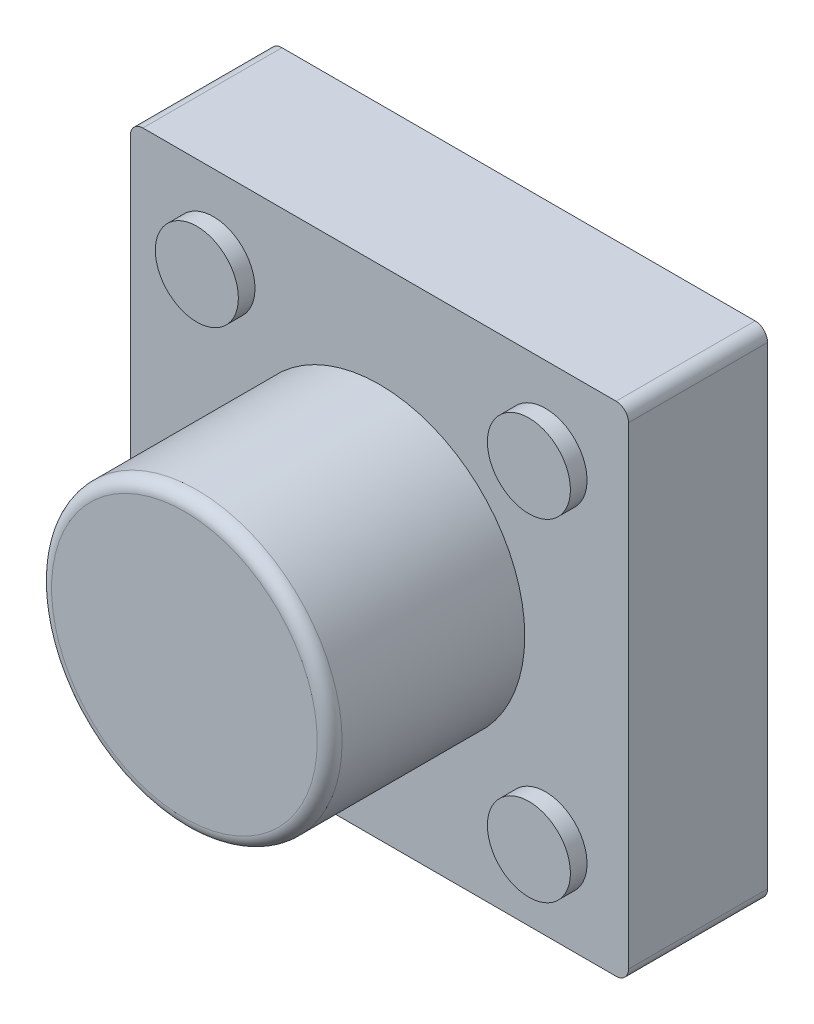
SolidWorks part; units mm, degrees
ref_plane "Front Plane" through (0, 0, 0) normal (0, 0, 1) x (1, 0, 0)
ref_plane "Top Plane" through (0, 0, 0) normal (0, 1, 0) x (1, 0, 0)
ref_plane "Right Plane" through (0, 0, 0) normal (1, 0, 0) x (0, 0, -1)
sketch "Sketch2" plane through (0, 0, 0) normal (0, 0, 1) x (1, 0, 0)
  line L1 (0, 0) -> (12, 0)
  line L2 (0, 0) -> (0, 12)
  line L3 (0, 12) -> (12, 12)
  line L4 (12, 0) -> (12, 12)
  dimension "D1" = 12
  dimension "D2" = 12
extrude "Boss-Extrude1" add sketch "Sketch2" along normal blind 3.35
sketch "Sketch3" plane through (0, 0, 3.35) normal (0, 0, 1) x (1, 0, 0)
  line L0 (6, 12) -> (6, 0) construction
  line L1 (12, 12) -> (0, 12) construction
  line L2 (0, 0) -> (12, 0) construction
  line L4 (0, 12) -> (0, 0) construction
  line L5 (0, 6) -> (12, 6) construction
  line L6 (12, 0) -> (12, 12) construction
  circle A0 centre (6, 6) radius 3.5
  dimension "D1" = 7
extrude "Boss-Extrude2" add sketch "Sketch3" along normal blind 4.7
ref_plane "Plane1" through (0, 6, 0) normal (0, 1, 0) x (1, 0, 0)
ref_plane "Plane2" through (6, 0, 0) normal (1, 0, 0) x (0, 0, -1)
ref_plane "Plane3" through (12, 0, 0) normal (1, 0, 0) x (0, 0, -1)
sketch "Sketch4" plane through (12, 0, 0) normal (1, 0, 0) x (0, 0, -1)
  line L0 (-0.6, 12) -> (-0.6, 9.45)
  line L1 (-3.35, 12) -> (0, 12) construction
  line L2 (-0.6, 9.45) -> (0.68, 9.45)
  line L3 (0.68, 9.45) -> (1.8, 9.95)
  line L4 (1.8, 9.95) -> (3.5, 9.45)
  line L5 (3.2945, 6) -> (-3.2945, 6) construction
  line L6 (0, 0) -> (0, 12) construction
  dimension "D1" = 3.95
  dimension "D2" = 1.8
  dimension "D3" = 0.68
  dimension "D4" = 3.5
  dimension "D5" = 3.45
  dimension "D6" = 4.1
fillet "Fillet1" radius 0.3 5 edges at (9.5, 6, 8.05) (0, 0, 1.675) (0, 12, 1.675) (12, 12, 1.675) (12, 0, 1.675)
sketch "Sketch5" plane through (0, 0, 3.35) normal (0, 0, 1) x (1, 0, 0)
  line L0 (2, 12) -> (2, 0.0702) construction
  line L1 (11.7, 12) -> (0.3, 12) construction
  line L2 (10, 12) -> (10, 0) construction
  line L3 (0.3, 0) -> (11.7, 0) construction
  line L4 (12, 0.3) -> (12, 11.7) construction
  line L5 (12, 2) -> (0, 2) construction
  line L6 (0, 11.7) -> (0, 0.3) construction
  line L8 (12, 10) -> (0, 10) construction
  circle A0 centre (2, 10) radius 1
  circle A1 centre (10, 10) radius 1
  circle A2 centre (10, 2) radius 1
  circle A3 centre (2, 2) radius 1
  point P28 (0, 0)
  point P29 (4.885, 0)
  point P30 (1.105, 0)
  point P31 (0, 0)
  point P32 (1.105, 5.99)
  point P33 (1.105, 12)
  point P34 (0, 0)
  point P35 (10.5357, 12)
  point P36 (0, 0)
  point P37 (2.1782, 0.0702)
  dimension "D3" = 2
  dimension "D1" = 2
  dimension "D2" = 2
  dimension "D4" = 2
  dimension "D5" = 2
extrude "Boss-Extrude3" add sketch "Sketch5" along normal blind 0.4
